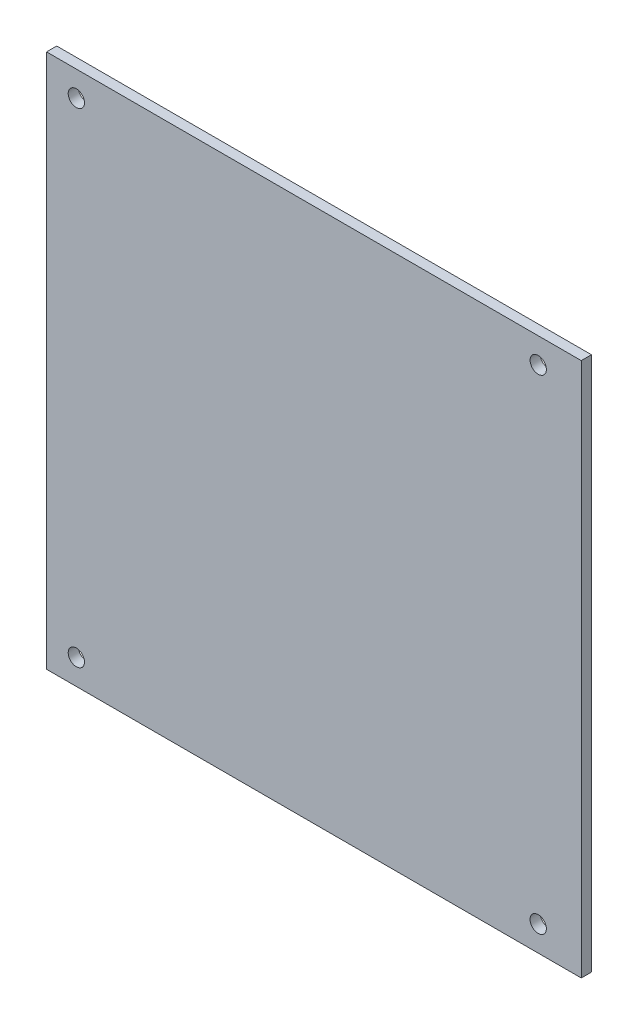
SolidWorks part; units mm, degrees
ref_plane "前视基准面" through (0, 0, 0) normal (0, 0, 1) x (1, 0, 0)
ref_plane "上视基准面" through (0, 0, 0) normal (0, 1, 0) x (1, 0, 0)
ref_plane "右视基准面" through (0, 0, 0) normal (1, 0, 0) x (0, 0, -1)
sketch "草图1" plane through (0, 0, 0) normal (0, 0, 1) x (1, 0, 0)
  line L0 (-50.85, 50.85) -> (50.85, 50.85) construction
  line L1 (0, 52.5) -> (52.5, 52.5)
  line L2 (52.5, 52.5) -> (52.5, -52.5)
  line L3 (52.5, -52.5) -> (-52.5, -52.5)
  line L4 (-52.5, -52.5) -> (-52.5, 52.5)
  line L5 (-52.5, 52.5) -> (0, 52.5)
  line L7 (-50.85, 50.85) -> (-50.85, -50.85) construction
  line L8 (-50.85, -50.85) -> (50.85, -50.85) construction
  line L9 (50.85, -50.85) -> (50.85, 50.85) construction
  line L10 (-46.65, 50.85) -> (-46.65, 47.55) construction
  line L11 (-46.65, 47.55) -> (-50.85, 47.55) construction
  line L12 (44.05, 50.85) -> (44.05, 47.55) construction
  circle A0 centre (-46.65, 47.55) radius 1.6
  circle A1 centre (44.05, 47.55) radius 1.6
  circle A2 centre (-46.65, -47.55) radius 1.6
  circle A3 centre (44.05, -47.55) radius 1.6
extrude "凸台-拉伸1" add sketch "草图1" along normal blind 2
